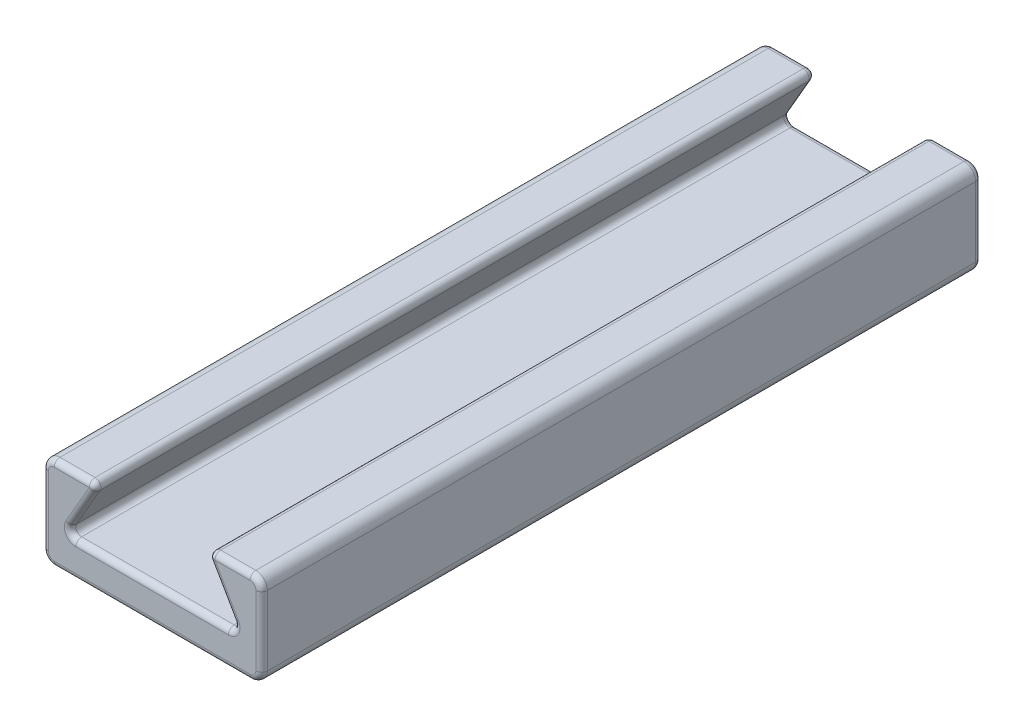
SolidWorks part; units mm, degrees
ref_plane "Front Plane" through (0, 0, 0) normal (0, 0, 1) x (1, 0, 0)
ref_plane "Top Plane" through (0, 0, 0) normal (0, 1, 0) x (1, 0, 0)
ref_plane "Right Plane" through (0, 0, 0) normal (1, 0, 0) x (0, 0, -1)
sketch "Sketch1" plane through (0, 0, 0) normal (0, 0, 1) x (0, 1, 0)
  line L0 (0, -16.8706) -> (0, -13.9839)
  line L1 (-5, 0) -> (-8, 0)
  line L2 (0, -13.9839) -> (-5, -16.8706)
  line L3 (-5, -16.8706) -> (-5, -2)
  line L4 (-5, -16.8706) -> (-5, -18.8706)
  line L5 (-5, -18.8706) -> (0, -18.8706)
  line L6 (0, -18.8706) -> (0, -16.8706)
  line L7 (-8, 0) -> (-8, -18.8706)
  line L8 (-8, -18.8706) -> (-5, -18.8706)
  line L12 (-5, -2) -> (0, -4.8868)
  line L13 (0, -4.8868) -> (0, -2)
  line L15 (0, -2) -> (-5, -2)
  line L16 (-5, -16.8706) -> (0, -16.8706)
  line L19 (-5, -2) -> (-5, 0)
  line L20 (-5, 0) -> (0, 0)
  line L21 (0, 0) -> (0, -2)
  dimension "D2" = 5
  dimension "D3" = 60
  dimension "D4" = 2
  dimension "D1" = 14.8706
  dimension "D5" = 3
extrude "Boss-Extrude1" add sketch "Sketch1" along normal blind 62 contours L21 L20 L19 L15 | L13 L15 L12 | L3 L19 L1 L7 L8 L4 | L2 L16 L0 | L16 L4 L5 L6
fillet "Fillet1" radius 0.5 4 edges at (16.8706, -5, 31) (2, -5, 31) (13.9839, 0, 31) (4.8868, 0, 31)
fillet "Fillet2" radius 1 4 edges at (18.8706, 0, 31) (18.8706, -8, 31) (0, -8, 31) (0, 0, 31)
fillet "Fillet3" radius 0.5 32 edges at (0.2929, -7.7071, 62) (0.2929, -7.7071, 0) (9.4353, -8, 0) (9.4353, -8, 62) (18.5777, -7.7071, 62) (18.5777, -7.7071, 0) (18.8706, -4, 0) (18.8706, -4, 62) (18.5777, -0.2929, 62) (18.5777, -0.2929, 0) (16.3603, 0, 62) (16.3603, 0, 0) (14.4169, -0.25, 62) (14.4169, -0.25, 0) (15.4272, -2.5, 0) (15.4272, -2.5, 62) (16.4376, -4.75, 62) (16.4376, -4.75, 0) (9.4353, -5, 62) (9.4353, -5, 0) (2.433, -4.75, 62) (2.433, -4.75, 0) (3.4434, -2.5, 62) (3.4434, -2.5, 0) (4.4537, -0.25, 62) (4.4537, -0.25, 0) (2.5104, 0, 0) (2.5104, 0, 62) (0.2929, -0.2929, 62) (0.2929, -0.2929, 0) (0, -4, 0) (0, -4, 62)
